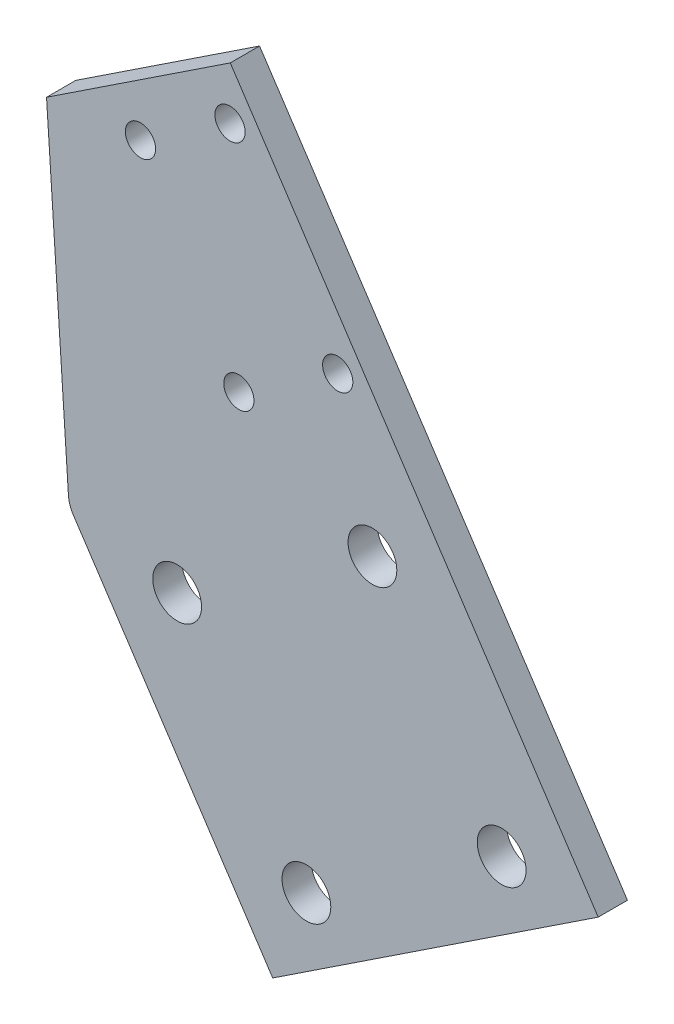
SolidWorks part; units mm, degrees
material "片状模压塑料板材"
ref_plane "前视基准面" through (0, 0, 0) normal (0, 0, 1) x (1, 0, 0)
ref_plane "上视基准面" through (0, 0, 0) normal (0, 1, 0) x (1, 0, 0)
ref_plane "右视基准面" through (0, 0, 0) normal (1, 0, 0) x (0, 0, -1)
other "Configuration Table"
sketch "草图1" plane through (0, 0, 0) normal (0, 0, 1) x (1, 0, 0)
  line L0 (6.9867, -53.1619) -> (35.3388, -34.3961)
  line L1 (36.1847, -30.2386) -> (-18.4571, 52.3161)
  line L2 (-22.6145, 53.1619) -> (-35.3388, 44.7399)
  line L3 (-36.6766, 42.0418) -> (-34.2027, 4.3492)
  line L4 (-33.7108, 2.8899) -> (2.8293, -52.3161)
  line L5 (0, 0) -> (0, -73.4856) construction
  arc A0 (7.9915, -42.9033) -> (5.4898, -44.5591) centre (6.7407, -43.7312) ccw
  arc A1 (35.3388, -34.3961) -> (36.1847, -30.2386) centre (33.683, -31.8944) ccw
  arc A2 (-18.4571, 52.3161) -> (-22.6145, 53.1619) centre (-20.9587, 50.6603) ccw
  arc A3 (-35.3388, 44.7399) -> (-36.6766, 42.0418) centre (-33.683, 42.2383) ccw
  arc A4 (-34.2027, 4.3492) -> (-33.7108, 2.8899) centre (-31.2091, 4.5457) ccw
  arc A5 (2.8293, -52.3161) -> (6.9867, -53.1619) centre (5.3309, -50.6603) ccw
  arc A6 (5.4898, -44.5591) -> (7.9915, -42.9033) centre (6.7407, -43.7312) ccw
  arc A7 (28.0047, -29.6568) -> (25.5031, -31.3126) centre (26.7539, -30.4847) ccw
  arc A8 (25.5031, -31.3126) -> (28.0047, -29.6568) centre (26.7539, -30.4847) ccw
  arc A9 (20.2776, -17.9824) -> (17.776, -19.6382) centre (19.0268, -18.8103) ccw
  arc A10 (17.776, -19.6382) -> (20.2776, -17.9824) centre (19.0268, -18.8103) ccw
  arc A11 (0.2644, -31.2289) -> (-2.2373, -32.8847) centre (-0.9865, -32.0568) ccw
  arc A12 (-2.2373, -32.8847) -> (0.2644, -31.2289) centre (-0.9865, -32.0568) ccw
  arc A13 (-7.7327, -17.3347) -> (-11.9022, -20.0944) centre (-9.8175, -18.7146) ccw
  arc A14 (-11.9022, -20.0944) -> (-7.7327, -17.3347) centre (-9.8175, -18.7146) ccw
  arc A15 (12.2805, -4.0883) -> (8.1111, -6.8479) centre (10.1958, -5.4681) ccw
  arc A16 (8.1111, -6.8479) -> (12.2805, -4.0883) centre (10.1958, -5.4681) ccw
  arc A17 (-20.9792, 2.6785) -> (-25.1487, -0.0812) centre (-23.0639, 1.2987) ccw
  arc A18 (-25.1487, -0.0812) -> (-20.9792, 2.6785) centre (-23.0639, 1.2987) ccw
  arc A19 (-0.966, 15.925) -> (-5.1354, 13.1653) centre (-3.0507, 14.5452) ccw
  arc A20 (-5.1354, 13.1653) -> (-0.966, 15.925) centre (-3.0507, 14.5452) ccw
  arc A21 (-5.3159, 29.8347) -> (-7.9009, 28.1237) centre (-6.6084, 28.9792) ccw
  arc A22 (-7.9009, 28.1237) -> (-5.3159, 29.8347) centre (-6.6084, 28.9792) ccw
  arc A23 (-15.4465, 23.1294) -> (-18.0316, 21.4184) centre (-16.7391, 22.2739) ccw
  arc A24 (-18.0316, 21.4184) -> (-15.4465, 23.1294) centre (-16.7391, 22.2739) ccw
  arc A25 (-16.3546, 46.5125) -> (-18.9396, 44.8015) centre (-17.6471, 45.657) ccw
  arc A26 (-18.9396, 44.8015) -> (-16.3546, 46.5125) centre (-17.6471, 45.657) ccw
  arc A27 (-25.5273, 40.4412) -> (-28.1124, 38.7302) centre (-26.8199, 39.5857) ccw
  arc A28 (-28.1124, 38.7302) -> (-25.5273, 40.4412) centre (-26.8199, 39.5857) ccw
  dimension "D1" = 105
  dimension "D2" = 15.259
  dimension "D3" = 37.7736
  dimension "D4" = 66.2033
  dimension "D5" = 34
  dimension "D6" = 150.255
  dimension "D7" = 119.745
  dimension "D8" = 90
extrude "凸台-拉伸1" add sketch "草图1" along normal blind 3
sketch "草图2" plane through (0, 0, 3) normal (0, 0, 1) x (1, 0, 0)
  line L0 (-17.6185, 51.0491) -> (-36.4497, 38.585)
  line L1 (36.1847, -30.2386) -> (-18.4571, 52.3161) construction
  line L2 (-36.6766, 42.0418) -> (-34.2027, 4.3492) construction
  line L3 (-36.4497, 38.585) -> (-39.0803, 42.5594)
  line L4 (-39.0803, 42.5594) -> (-20.2491, 55.0235)
  line L5 (-20.2491, 55.0235) -> (-17.6185, 51.0491)
  line L6 (22.2942, -9.2524) -> (-11.0612, -31.3299)
  line L7 (-33.7108, 2.8899) -> (2.8293, -52.3161) construction
  line L8 (-11.0612, -31.3299) -> (5.024, -55.632)
  line L9 (5.024, -55.632) -> (41.7405, -31.3299)
  line L10 (41.7405, -31.3299) -> (22.2942, -9.2524)
extrude "切除-拉伸1" cut sketch "草图2" against normal blind 10
sketch "草图3" plane through (0, 0, 3) normal (0, 0, 1) x (1, 0, 0)
  line L0 (-13.2689, -27.9944) -> (20.0865, -5.9169)
  line L1 (-33.7108, 2.8899) -> (-11.0612, -31.3299) construction
  line L2 (22.2942, -9.2524) -> (-17.6185, 51.0491) construction
  line L3 (22.2942, -9.2524) -> (-11.0612, -31.3299) construction
  line L4 (-13.2689, -27.9944) -> (-14.1314, -36.9306)
  line L5 (-14.1314, -36.9306) -> (39.3394, -11.5084)
  line L6 (39.3394, -11.5084) -> (20.0865, -5.9169)
  dimension "D1" = 4
extrude "切除-拉伸2" cut sketch "草图3" against normal blind 10
